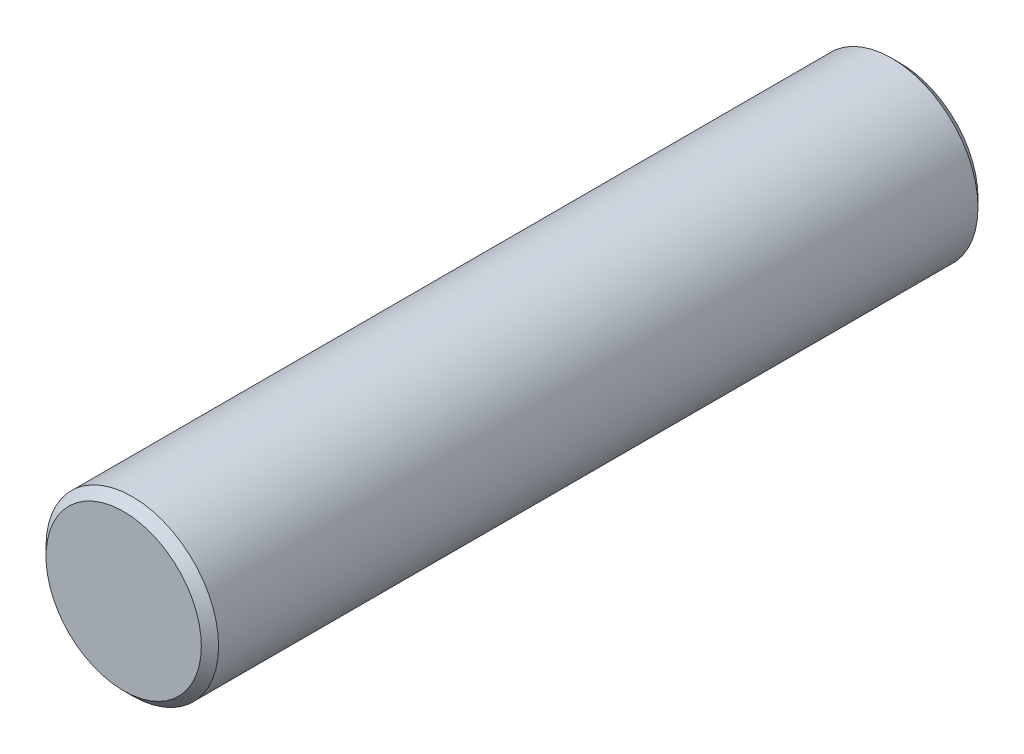
SolidWorks part; units mm, degrees
ref_plane "Front Plane" through (0, 0, 0) normal (1, 0, 0) x (0, 1, 0)
ref_plane "Top Plane" through (0, 0, 0) normal (0, 0, 1) x (0, 1, 0)
ref_plane "Right Plane" through (0, 0, 0) normal (0, 1, 0) x (-1, 0, 0)
sketch "Sketch1" plane through (0, 0, 0) normal (0, 0, 1) x (0, 1, 0)
  circle A0 centre (0, 0) radius 2
  dimension "D1" = 4
extrude "Boss-Extrude1" add sketch "Sketch1" along normal mid plane 18
chamfer "Chamfer1" distance 0.2 angle 45 2 edges at (2, 0, -9) (2, 0, 9)
